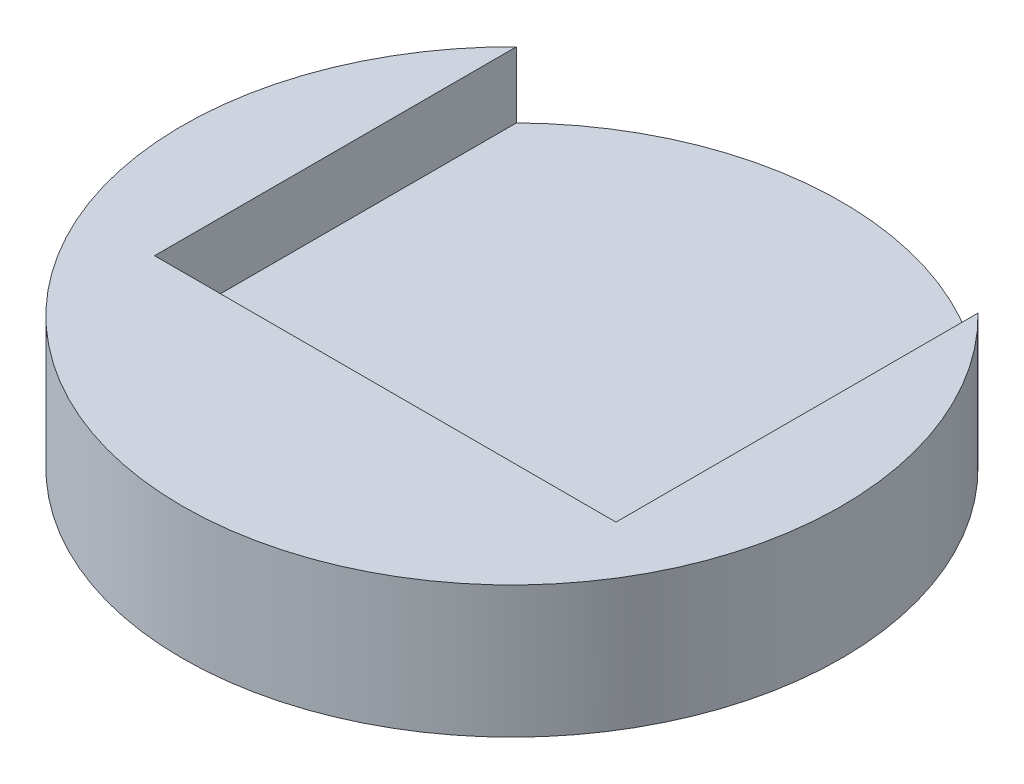
SolidWorks part; units mm, degrees
ref_plane "Front Plane" through (0, 0, 0) normal (0, 0, 1) x (1, 0, 0)
ref_plane "Top Plane" through (0, 0, 0) normal (0, 1, 0) x (1, 0, 0)
ref_plane "Right Plane" through (0, 0, 0) normal (1, 0, 0) x (0, 0, -1)
sketch "Sketch1" plane through (0, 0, 0) normal (0, 1, 0) x (1, 0, 0)
  circle A0 centre (0, 0) radius 50
extrude "Boss-Extrude1" add sketch "Sketch1" along normal blind 20
sketch "Sketch2" plane through (0, 20, 0) normal (0, 1, 0) x (1, 0, 0)
  line L0 (-35.0151, 35.7978) -> (34.9849, 35.7978)
  line L1 (34.9849, 35.7978) -> (34.9849, -19.2022)
  line L2 (34.9849, -19.2022) -> (-35.0151, -19.2022)
  line L3 (-35.0151, -19.2022) -> (-35.0151, 35.7978)
extrude "Cut-Extrude1" cut sketch "Sketch2" against normal blind 10 contours L3 L0 L1 L2
sketch "Sketch3" plane through (0, 20, 0) normal (0, 1, 0) x (1, 0, 0)
  line L0 (-35.0151, 35.6923) -> (34.9849, 35.722)
  arc A0 (-35.0151, 35.6923) -> (34.9849, 35.722) centre (0, 0) cw
extrude "Cut-Extrude3" cut sketch "Sketch3" against normal blind 10
sketch "Sketch6" plane through (0, 20, 0) normal (0, 1, 0) x (1, 0, 0)
  circle A0 centre (0, 0) radius 50
  circle A1 centre (0, 0) radius 50
  circle A2 centre (0, 0) radius 50
